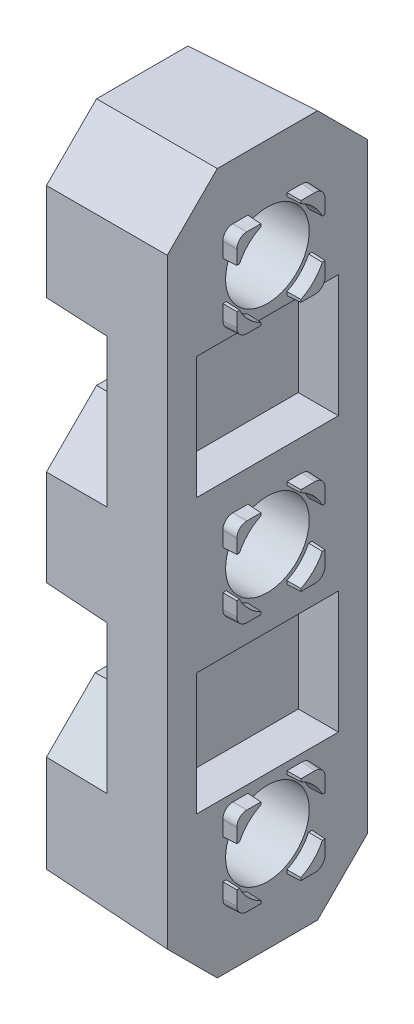
SolidWorks part; units mm, degrees
ref_plane "Front Plane" through (0, 0, 0) normal (0, 0, 1) x (1, 0, 0)
ref_plane "Top Plane" through (0, 0, 0) normal (0, 1, 0) x (1, 0, 0)
ref_plane "Right Plane" through (0, 0, 0) normal (1, 0, 0) x (0, 0, -1)
ref_plane "Plane1" through (88.9762, 0, 0) normal (1, 0, 0) x (0, 0, -1)
sketch "Sketch1" plane through (88.9762, 0, 0) normal (1, 0, 0) x (0, 0, -1)
  line L0 (7.8417, 8.8578) -> (17.5583, 8.8578)
  line L1 (17.5583, 8.8578) -> (17.5583, 43.9743)
  line L2 (17.5583, 43.9743) -> (7.8417, 43.9743)
  line L3 (7.8417, 43.9743) -> (7.8417, 8.8578)
extrude "Boss-Extrude1" add sketch "Sketch1" against normal blind 6.35
sketch "Sketch2" plane through (82.6262, 0, 0) normal (-1, 0, 0) x (0, 0, 1)
  line L0 (-7.8417, 36.5093) -> (-10.3153, 34.0358)
  line L1 (-10.3153, 34.0358) -> (-11.7, 34.0358)
  line L2 (-11.7, 34.0358) -> (-11.7, 31.3853)
  line L3 (-11.7, 31.3853) -> (-10.3802, 31.3853)
  line L4 (-10.3802, 31.3853) -> (-7.8417, 28.8468)
  line L5 (-7.8417, 28.8468) -> (-7.8417, 36.5093)
extrude "Cut-Extrude1" cut sketch "Sketch2" against normal blind 3.175
sketch "Sketch3" plane through (82.6262, 0, 0) normal (-1, 0, 0) x (0, 0, 1)
  line L0 (-7.8417, 23.9852) -> (-10.3802, 21.4468)
  line L1 (-10.3802, 21.4468) -> (-11.7, 21.4468)
  line L2 (-11.7, 21.4468) -> (-11.7, 18.7963)
  line L3 (-11.7, 18.7963) -> (-10.3153, 18.7963)
  line L4 (-10.3153, 18.7963) -> (-7.8417, 16.3228)
  line L5 (-7.8417, 16.3228) -> (-7.8417, 23.9852)
extrude "Cut-Extrude2" cut sketch "Sketch3" against normal blind 3.175
sketch "Sketch4" plane through (82.6262, 0, 0) normal (-1, 0, 0) x (0, 0, 1)
  line L0 (-17.5583, 16.3228) -> (-15.0847, 18.7963)
  line L1 (-15.0847, 18.7963) -> (-13.7, 18.7963)
  line L2 (-13.7, 18.7963) -> (-13.7, 21.4468)
  line L3 (-13.7, 21.4468) -> (-15.0198, 21.4468)
  line L4 (-15.0198, 21.4468) -> (-17.5583, 23.9852)
  line L5 (-17.5583, 23.9852) -> (-17.5583, 16.3228)
extrude "Cut-Extrude3" cut sketch "Sketch4" against normal blind 3.175
sketch "Sketch5" plane through (82.6262, 0, 0) normal (-1, 0, 0) x (0, 0, 1)
  line L0 (-17.5583, 28.8468) -> (-15.0198, 31.3853)
  line L1 (-15.0198, 31.3853) -> (-13.7, 31.3853)
  line L2 (-13.7, 31.3853) -> (-13.7, 34.0358)
  line L3 (-13.7, 34.0358) -> (-15.0847, 34.0358)
  line L4 (-15.0847, 34.0358) -> (-17.5583, 36.5093)
  line L5 (-17.5583, 36.5093) -> (-17.5583, 28.8468)
extrude "Cut-Extrude4" cut sketch "Sketch5" against normal blind 3.175
sketch "Sketch6" plane through (88.9762, 0, 0) normal (1, 0, 0) x (0, 0, -1)
  line L0 (11.7094, 24.3276) -> (11.7094, 24.1554)
  line L1 (11.7094, 24.1554) -> (10.4394, 24.1554)
  line L2 (10.4394, 24.1554) -> (10.4394, 25.4254)
  line L3 (10.4394, 25.4254) -> (10.6116, 25.4254)
  arc A0 (10.6116, 25.4254) -> (11.7094, 24.3276) centre (12.7, 26.416) ccw
extrude "Boss-Extrude2" add sketch "Sketch6" along normal blind 0.6858 draft 2
sketch "Sketch7" plane through (88.9762, 0, 0) normal (1, 0, 0) x (0, 0, -1)
  line L0 (14.7884, 25.4254) -> (14.9606, 25.4254)
  line L1 (14.9606, 25.4254) -> (14.9606, 24.1554)
  line L2 (14.9606, 24.1554) -> (13.6906, 24.1554)
  line L3 (13.6906, 24.1554) -> (13.6906, 24.3276)
  arc A0 (13.6906, 24.3276) -> (14.7884, 25.4254) centre (12.7, 26.416) ccw
extrude "Boss-Extrude3" add sketch "Sketch7" along normal blind 0.6858 draft 2
sketch "Sketch8" plane through (88.9762, 0, 0) normal (1, 0, 0) x (0, 0, -1)
  line L0 (13.6906, 28.5044) -> (13.6906, 28.6766)
  line L1 (13.6906, 28.6766) -> (14.9606, 28.6766)
  line L2 (14.9606, 28.6766) -> (14.9606, 27.4066)
  line L3 (14.9606, 27.4066) -> (14.7884, 27.4066)
  arc A0 (14.7884, 27.4066) -> (13.6906, 28.5044) centre (12.7, 26.416) ccw
extrude "Boss-Extrude4" add sketch "Sketch8" along normal blind 0.6858 draft 2
sketch "Sketch9" plane through (88.9762, 0, 0) normal (1, 0, 0) x (0, 0, -1)
  line L0 (10.6116, 27.4066) -> (10.4394, 27.4066)
  line L1 (10.4394, 27.4066) -> (10.4394, 28.6766)
  line L2 (10.4394, 28.6766) -> (11.7094, 28.6766)
  line L3 (11.7094, 28.6766) -> (11.7094, 28.5044)
  arc A0 (11.7094, 28.5044) -> (10.6116, 27.4066) centre (12.7, 26.416) ccw
extrude "Boss-Extrude5" add sketch "Sketch9" along normal blind 0.6858 draft 2
sketch "Sketch10" plane through (88.9762, 0, 0) normal (1, 0, 0) x (0, 0, -1)
  line L0 (11.7094, 37.0276) -> (11.7094, 36.8554)
  line L1 (11.7094, 36.8554) -> (10.4394, 36.8554)
  line L2 (10.4394, 36.8554) -> (10.4394, 38.1254)
  line L3 (10.4394, 38.1254) -> (10.6116, 38.1254)
  arc A0 (10.6116, 38.1254) -> (11.7094, 37.0276) centre (12.7, 39.116) ccw
extrude "Boss-Extrude6" add sketch "Sketch10" along normal blind 0.6858 draft 2
sketch "Sketch11" plane through (88.9762, 0, 0) normal (1, 0, 0) x (0, 0, -1)
  line L0 (14.7884, 38.1254) -> (14.9606, 38.1254)
  line L1 (14.9606, 38.1254) -> (14.9606, 36.8554)
  line L2 (14.9606, 36.8554) -> (13.6906, 36.8554)
  line L3 (13.6906, 36.8554) -> (13.6906, 37.0276)
  arc A0 (13.6906, 37.0276) -> (14.7884, 38.1254) centre (12.7, 39.116) ccw
extrude "Boss-Extrude7" add sketch "Sketch11" along normal blind 0.6858 draft 2
sketch "Sketch12" plane through (88.9762, 0, 0) normal (1, 0, 0) x (0, 0, -1)
  line L0 (13.6906, 41.2044) -> (13.6906, 41.3766)
  line L1 (13.6906, 41.3766) -> (14.9606, 41.3766)
  line L2 (14.9606, 41.3766) -> (14.9606, 40.1066)
  line L3 (14.9606, 40.1066) -> (14.7884, 40.1066)
  arc A0 (14.7884, 40.1066) -> (13.6906, 41.2044) centre (12.7, 39.116) ccw
extrude "Boss-Extrude8" add sketch "Sketch12" along normal blind 0.6858 draft 2
sketch "Sketch13" plane through (88.9762, 0, 0) normal (1, 0, 0) x (0, 0, -1)
  line L0 (10.6116, 40.1066) -> (10.4394, 40.1066)
  line L1 (10.4394, 40.1066) -> (10.4394, 41.3766)
  line L2 (10.4394, 41.3766) -> (11.7094, 41.3766)
  line L3 (11.7094, 41.3766) -> (11.7094, 41.2044)
  arc A0 (11.7094, 41.2044) -> (10.6116, 40.1066) centre (12.7, 39.116) ccw
extrude "Boss-Extrude9" add sketch "Sketch13" along normal blind 0.6858 draft 2
sketch "Sketch14" plane through (88.9762, 0, 0) normal (1, 0, 0) x (0, 0, -1)
  line L0 (11.7094, 11.6276) -> (11.7094, 11.4554)
  line L1 (11.7094, 11.4554) -> (10.4394, 11.4554)
  line L2 (10.4394, 11.4554) -> (10.4394, 12.7254)
  line L3 (10.4394, 12.7254) -> (10.6116, 12.7254)
  arc A0 (10.6116, 12.7254) -> (11.7094, 11.6276) centre (12.7, 13.716) ccw
extrude "Boss-Extrude10" add sketch "Sketch14" along normal blind 0.6858 draft 2
sketch "Sketch15" plane through (88.9762, 0, 0) normal (1, 0, 0) x (0, 0, -1)
  line L0 (14.7884, 12.7254) -> (14.9606, 12.7254)
  line L1 (14.9606, 12.7254) -> (14.9606, 11.4554)
  line L2 (14.9606, 11.4554) -> (13.6906, 11.4554)
  line L3 (13.6906, 11.4554) -> (13.6906, 11.6276)
  arc A0 (13.6906, 11.6276) -> (14.7884, 12.7254) centre (12.7, 13.716) ccw
extrude "Boss-Extrude11" add sketch "Sketch15" along normal blind 0.6858 draft 2
sketch "Sketch16" plane through (88.9762, 0, 0) normal (1, 0, 0) x (0, 0, -1)
  line L0 (13.6906, 15.8044) -> (13.6906, 15.9766)
  line L1 (13.6906, 15.9766) -> (14.9606, 15.9766)
  line L2 (14.9606, 15.9766) -> (14.9606, 14.7066)
  line L3 (14.9606, 14.7066) -> (14.7884, 14.7066)
  arc A0 (14.7884, 14.7066) -> (13.6906, 15.8044) centre (12.7, 13.716) ccw
extrude "Boss-Extrude12" add sketch "Sketch16" along normal blind 0.6858 draft 2
sketch "Sketch17" plane through (88.9762, 0, 0) normal (1, 0, 0) x (0, 0, -1)
  line L0 (10.6116, 14.7066) -> (10.4394, 14.7066)
  line L1 (10.4394, 14.7066) -> (10.4394, 15.9766)
  line L2 (10.4394, 15.9766) -> (11.7094, 15.9766)
  line L3 (11.7094, 15.9766) -> (11.7094, 15.8044)
  arc A0 (11.7094, 15.8044) -> (10.6116, 14.7066) centre (12.7, 13.716) ccw
extrude "Boss-Extrude13" add sketch "Sketch17" along normal blind 0.6858 draft 2
sketch "Sketch18" plane through (88.9762, 0, 0) normal (1, 0, 0) x (0, 0, -1)
  line L0 (9.1, 16.366) -> (16.3, 16.366)
  line L1 (16.3, 16.366) -> (16.3, 22.566)
  line L2 (16.3, 22.566) -> (9.1, 22.566)
  line L3 (9.1, 22.566) -> (9.1, 16.366)
extrude "Cut-Extrude5" cut sketch "Sketch18" against normal blind 2.032
sketch "Sketch19" plane through (88.9762, 0, 0) normal (1, 0, 0) x (0, 0, -1)
  line L0 (9.1, 36.466) -> (9.1, 30.266)
  line L1 (9.1, 30.266) -> (16.3, 30.266)
  line L2 (16.3, 30.266) -> (16.3, 36.466)
  line L3 (16.3, 36.466) -> (9.1, 36.466)
extrude "Cut-Extrude6" cut sketch "Sketch19" against normal blind 2.032
draft "Draft1" type of draft neutral plane draft angle 2.827 faces to draft 4 face at (84.2137, 30.116, -9.111) face at (84.2137, 22.716, -9.111) face at (84.2137, 22.716, -16.289) face at (84.2137, 30.116, -16.289) neutral plane through (82.6262, 0, 0) neutral plane normal (-1, 0, 0) parameters "D1"=2.827
draft "Draft2" type of draft neutral plane draft angle 2 faces to draft 16 face at (85.8012, 43.9743, -12.7) face at (84.2137, 35.2725, -9.0785) face at (84.2137, 34.0358, -11.0076) face at (84.2137, 31.3853, -10.9847) face at (84.2137, 21.4468, -10.9847) face at (84.2137, 18.7963, -11.0076) face at (84.2137, 17.5595, -9.0785) face at (84.7429, 26.416, -7.8417) face at (85.8012, 8.8578, -12.7) face at (84.2137, 17.5595, -16.3215) face at (84.2137, 18.7963, -14.3924) face at (84.2137, 21.4468, -14.4153) face at (84.2137, 31.3853, -14.4153) face at (84.2137, 34.0358, -14.3924) face at (84.2137, 35.2725, -16.3215) face at (84.7429, 26.416, -17.5583) neutral plane through (82.6262, 0, 0) neutral plane normal (-1, 0, 0) parameters "D1"=2
hole_wizard "#6 Clearance Hole1" positions "Sketch21" profile "Sketch20" hole size "#6" standard "ANSI Inch"
sketch "Sketch21" plane through (82.6262, 0, 0) normal (-1, 0, 0) x (0, 0, 1)
  point P0 (-12.7, 26.416)
  point P1 (-12.7, 13.716)
  point P2 (-12.7, 39.116)
sketch "Sketch20" plane through (82.6262, 26.416, -12.7) normal (0, 1, 0) x (0, 0, 1)
  line L0 (0, 0) -> (0, 7.0358)
  line L1 (0, 7.0358) -> (2.1209, 7.0358)
  line L2 (2.1209, 7.0358) -> (2.1209, 0)
  line L5 (2.1209, 0) -> (0, 0)
  line L11 (0, -6.35) -> (0, 107.95) construction
  dimension "Thru Hole Dia." = 4.2418
  dimension "Thru Hole Depth" = 7.0358
chamfer "Chamfer1" distance 2.5369 angle 44.965 4 edges at (85.8012, 8.7469, -17.6691) (85.8012, 44.0851, -17.6691) (85.8012, 8.7469, -7.7309) (85.8012, 44.0851, -7.7309)
fillet "Fillet1" radius 0.508 12 edges at (89.3191, 41.3646, -10.4514) (89.3191, 15.9646, -10.4514) (89.3191, 11.4674, -14.9486) (89.3191, 24.1674, -10.4514) (89.3191, 41.3646, -14.9486) (89.3191, 24.1674, -14.9486) (89.3191, 11.4674, -10.4514) (89.3191, 28.6646, -14.9486) (89.3191, 15.9646, -14.9486) (89.3191, 36.8674, -10.4514) (89.3191, 36.8674, -14.9486) (89.3191, 28.6646, -10.4514)
